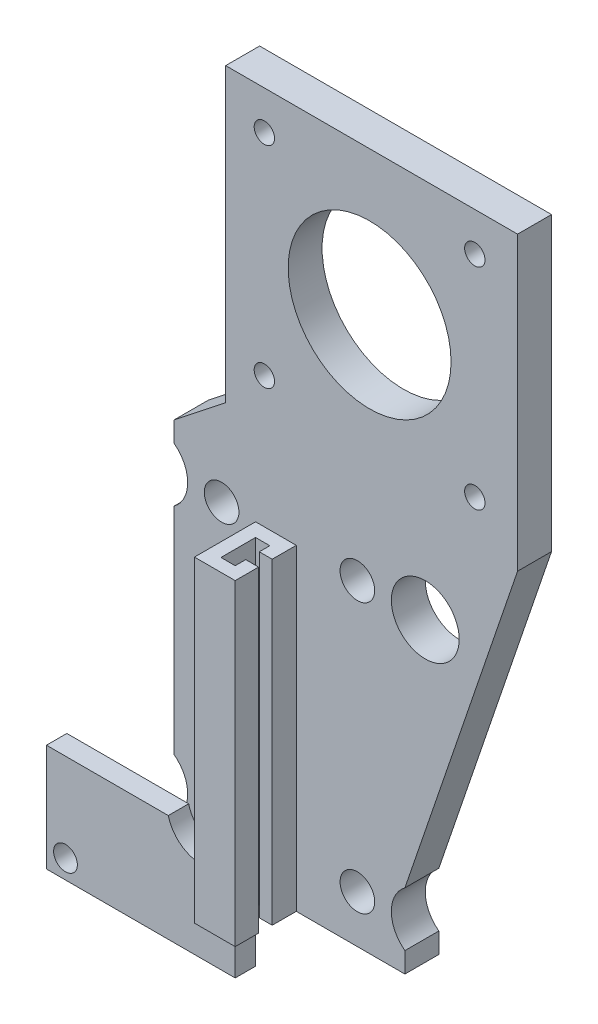
SolidWorks part; units mm, degrees
ref_plane "Front Plane" through (0, 0, 0) normal (0, 0, 1) x (1, 0, 0)
ref_plane "Top Plane" through (0, 0, 0) normal (0, 1, 0) x (1, 0, 0)
ref_plane "Right Plane" through (0, 0, 0) normal (1, 0, 0) x (0, 0, -1)
sketch "Sketch1" plane through (0, 0, 0) normal (0, 0, 1) x (1, 0, 0)
  line L0 (7, 46.7) -> (27, 46.7) construction
  line L1 (0, 0) -> (34, 0)
  line L2 (0, 0) -> (0, 3)
  line L3 (0, 53.7) -> (34, 53.7)
  line L4 (34, 0) -> (34, 3)
  line L5 (27, 46.7) -> (27, 7) construction
  line L6 (27, 7) -> (7, 7) construction
  line L7 (7, 7) -> (7, 46.7) construction
  line L8 (-3, 46.7) -> (37, 46.7) construction
  line L9 (37, 46.7) -> (37, 7) construction
  line L10 (37, 7) -> (-3, 7) construction
  line L11 (-3, 7) -> (-3, 46.7) construction
  line L12 (0, 50.7) -> (0, 53.7)
  line L13 (34, 50.7) -> (34, 53.7)
  line L14 (34, 11) -> (34, 42.7)
  line L15 (0, 11) -> (0, 42.7)
  circle A0 centre (7, 46.7) radius 2.55
  circle A1 centre (27, 46.7) radius 2.55
  circle A2 centre (7, 7) radius 2.55
  circle A3 centre (27, 7) radius 2.55
  arc A4 (0, 42.7) -> (0, 50.7) centre (-3, 46.7) ccw
  arc A5 (34, 50.7) -> (34, 42.7) centre (37, 46.7) ccw
  arc A6 (34, 11) -> (34, 3) centre (37, 7) ccw
  arc A7 (0, 3) -> (0, 11) centre (-3, 7) ccw
  dimension "D3" = 5.1
  dimension "D10" = 10
  dimension "D1" = 20
  dimension "D2" = 39.7
  dimension "D4" = 7
  dimension "D5" = 7
  dimension "D6" = 7
  dimension "D7" = 7
  dimension "D8" = 10
  dimension "D9" = 10
extrude "Boss-Extrude1" add sketch "Sketch1" along normal blind 5
sketch "Sketch2" plane through (0, 0, 5) normal (0, 0, 1) x (1, 0, 0)
  line L0 (7, 46.7) -> (27, 46.7) construction
  line L1 (12, 46.7) -> (18, 46.7)
  line L2 (12, 46.7) -> (12, 0)
  line L3 (12, 0) -> (18, 0)
  line L4 (18, 46.7) -> (18, 0)
  line L5 (7, 7) -> (27, 7) construction
  line L6 (17, 53.7) -> (17, 0) construction
  line L7 (34, 53.7) -> (0, 53.7) construction
  line L8 (0, 0) -> (34, 0) construction
  line L9 (0, 42.7) -> (0, 11) construction
  circle A0 centre (7, 7) radius 2.55 construction
  circle A1 centre (27, 7) radius 2.55 construction
  circle A2 centre (27, 46.7) radius 2.55 construction
  circle A3 centre (7, 46.7) radius 2.55 construction
  circle A4 centre (7, 7) radius 2.55
  circle A5 centre (27, 7) radius 2.55
  circle A6 centre (27, 46.7) radius 2.55
  circle A7 centre (7, 46.7) radius 2.55
  dimension "D1" = 6
  dimension "D2" = 12
extrude "Boss-Extrude2" add sketch "Sketch2" along normal blind 9 contours L4 L1 L2 L3
sketch "Sketch3" plane through (0, 0, 5) normal (0, 0, 1) x (1, 0, 0)
  line L0 (12, 46.7) -> (12, 0) construction
  line L1 (12, 5.8) -> (11.8539, 5.8)
  line L2 (12, 5.8) -> (12, -10)
  line L3 (12, -10) -> (-15.8, -10)
  line L4 (-15.8, 5.8) -> (-15.8, -10)
  line L6 (0, 0) -> (12, 0) construction
  line L7 (2.1461, 5.8) -> (-15.8, 5.8)
  circle A0 centre (7, 7) radius 4
  arc A1 (2.1461, 5.8) -> (11.8539, 5.8) centre (7, 7) ccw
  line M8 (12, 0) -> (12, 46.7)
  line M12 (0, 3) -> (0, 0)
  line M13 (0, 0) -> (12, 0)
  arc M23 (0, 11) -> (0, 3) centre (-3, 7) cw
  dimension "D3" = 8
  dimension "D5" = 10
  dimension "D1" = 27.8
  dimension "D2" = 15.8
  dimension "D4" = 10
extrude "Boss-Extrude3" add sketch "Sketch3" along normal blind 3 contours L1 L4 L3 L2 M13 M12 M23 | A0 L1 M23 M12 M13 M8
sketch "Sketch4" plane through (0, 0, 8) normal (0, 0, 1) x (1, 0, 0)
  line L0 (12, 5.8) -> (11.8539, 5.8) construction
  line L1 (-15.8, 5.8) -> (-15.8, -10) construction
  line L2 (12, 0) -> (12, -10) construction
  line L3 (12, -10) -> (-15.8, -10) construction
  circle A0 centre (9.2, 3) radius 1.75
  circle A1 centre (-13, -7.2) radius 1.75
  dimension "4" = 3.5
  dimension "D1" = 2.8
  dimension "D2" = 2.8
  dimension "D3" = 2.8
  dimension "D4" = 2.8
extrude "Cut-Extrude1" cut sketch "Sketch4" against normal through all
sketch "Sketch5" plane through (0, 46.7, 0) normal (0, 1, 0) x (1, 0, 0)
  line L0 (18, -8.55) -> (16.1, -8.55)
  line L9 (18, -14) -> (18, -5) construction
  line L10 (16.1, -8.55) -> (16.1, -7)
  line L11 (16.1, -7) -> (14, -7)
  line L12 (14, -7) -> (14, -12.1)
  line L13 (14, -12.1) -> (16.1, -12.1)
  line L14 (16.1, -12.1) -> (16.1, -10.55)
  line L15 (16.1, -10.55) -> (18, -10.55)
  line L16 (12, -9.55) -> (18, -9.55) construction
  line L18 (12, -5) -> (18, -5) construction
  dimension "D1" = 1.9
  dimension "D2" = 2
  dimension "D3" = 5.1
  dimension "D4" = 2.1
  dimension "D5" = 2
extrude "Cut-Extrude2" cut sketch "Sketch5" against normal through all and the other way through all
sketch "Sketch6" plane through (0, 0, 5) normal (0, 0, 1) x (1, 0, 0)
  line L0 (0, 53.7) -> (0, 50.7) construction
  line L5 (7.6, 102.7) -> (50.6, 102.7)
  line L6 (7.6, 102.7) -> (7.6, 59.7)
  line L7 (7.6, 59.7) -> (50.6, 59.7)
  line L8 (50.6, 102.7) -> (50.6, 59.7)
  line L9 (7.6, 59.7) -> (0, 53.7)
  line L10 (0, 53.7) -> (34, 53.7)
  line L11 (34, 53.7) -> (50.6, 59.7)
  circle A0 centre (27, 46.7) radius 2.55 construction
  line M23 (34, 53.7) -> (0, 53.7)
  dimension "D3" = 13
  dimension "D1" = 43
  dimension "D2" = 43
  dimension "D4" = 7.6
extrude "Boss-Extrude4" add sketch "Sketch6" against normal through all contours L8 L5 L6 L7 | L11 L7 L9 M23
sketch "Sketch8" plane through (0, 0, 5) normal (0, 0, 1) x (1, 0, 0)
  line L0 (13.3, 97) -> (44.3, 97) construction
  line L1 (44.3, 97) -> (44.3, 66) construction
  line L2 (44.3, 66) -> (13.3, 66) construction
  line L3 (13.3, 66) -> (13.3, 97) construction
  line L4 (7.6, 102.7) -> (7.6, 59.7) construction
  line L5 (7.6, 102.7) -> (50.6, 102.7) construction
  line L6 (28.8, 97) -> (28.8, 66) construction
  line L7 (13.3, 81.5) -> (44.3, 81.5) construction
  circle A0 centre (13.3, 97) radius 1.5
  circle A1 centre (44.3, 97) radius 1.5
  circle A2 centre (13.3, 66) radius 1.5
  circle A3 centre (44.3, 66) radius 1.5
  circle A4 centre (28.8, 81.5) radius 12
  point P18 (28.8, 81.5)
  dimension "D5" = 3
  dimension "D6" = 24
  dimension "D1" = 5.7
  dimension "D2" = 5.7
  dimension "D3" = 31
  dimension "D4" = 31
extrude "Cut-Extrude3" cut sketch "Sketch8" against normal through all
sketch "Sketch9" plane through (0, 0, 5) normal (0, 0, 1) x (1, 0, 0)
  line L0 (50.6, 59.7) -> (34, 11)
  circle A0 centre (37, 46.7) radius 5
  line M18 (34, 11) -> (34, 42.7)
  line M20 (34, 50.7) -> (34, 53.7)
  line M21 (34, 53.7) -> (50.6, 59.7)
  dimension "D1" = 10
extrude "Boss-Extrude5" add sketch "Sketch9" against normal up to surface (5 mm away) contours A0 L0 M18 M21 M20 up to face at (45.8, 97, 0)
